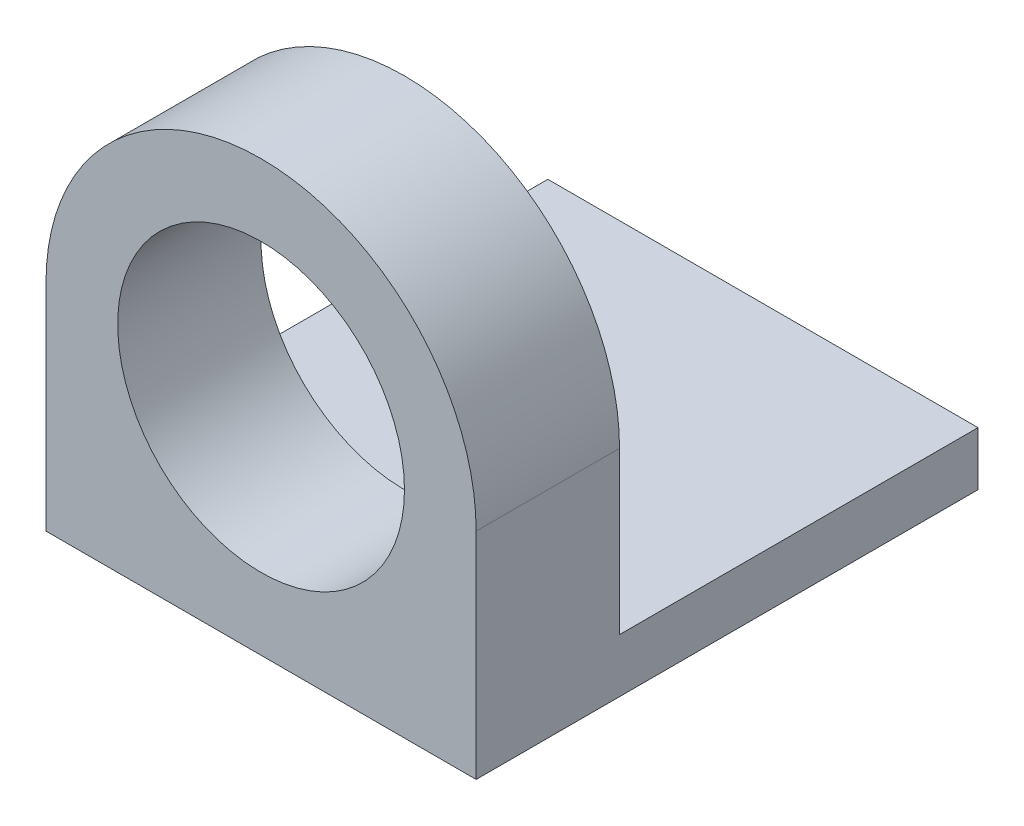
SolidWorks part; units mm, degrees
ref_plane "Front Plane" through (0, 0, 0) normal (0, 0, 1) x (1, 0, 0)
ref_plane "Top Plane" through (0, 0, 0) normal (0, 1, 0) x (1, 0, 0)
ref_plane "Right Plane" through (0, 0, 0) normal (1, 0, 0) x (0, 0, -1)
sketch "Sketch1" plane through (0, 0, 0) normal (0, 0, 1) x (1, 0, 0)
  line L0 (0, -6) -> (-6, -6)
  line L1 (-6, 0) -> (-6, -6)
  line L2 (6, 0) -> (6, -6)
  line L3 (0, -6) -> (6, -6)
  circle A0 centre (0, 0) radius 4
  arc A1 (6, 0) -> (-6, 0) centre (0, 0) ccw
  dimension "D1" = 8
  dimension "D2" = 12
extrude "Boss-Extrude1" add sketch "Sketch1" along normal blind 4
sketch "Sketch2" plane through (0, 0, 0) normal (0, 0, -1) x (-1, 0, 0)
  line L0 (6, 0) -> (6, -6) construction
  line L1 (-6, -6) -> (6, -6)
  line L2 (-6, -6) -> (-6, -4.5)
  line L3 (-6, -4.5) -> (6, -4.5)
  line L4 (6, -6) -> (6, -4.5)
  dimension "D1" = 1.5
extrude "Boss-Extrude2" add sketch "Sketch2" along normal blind 10
